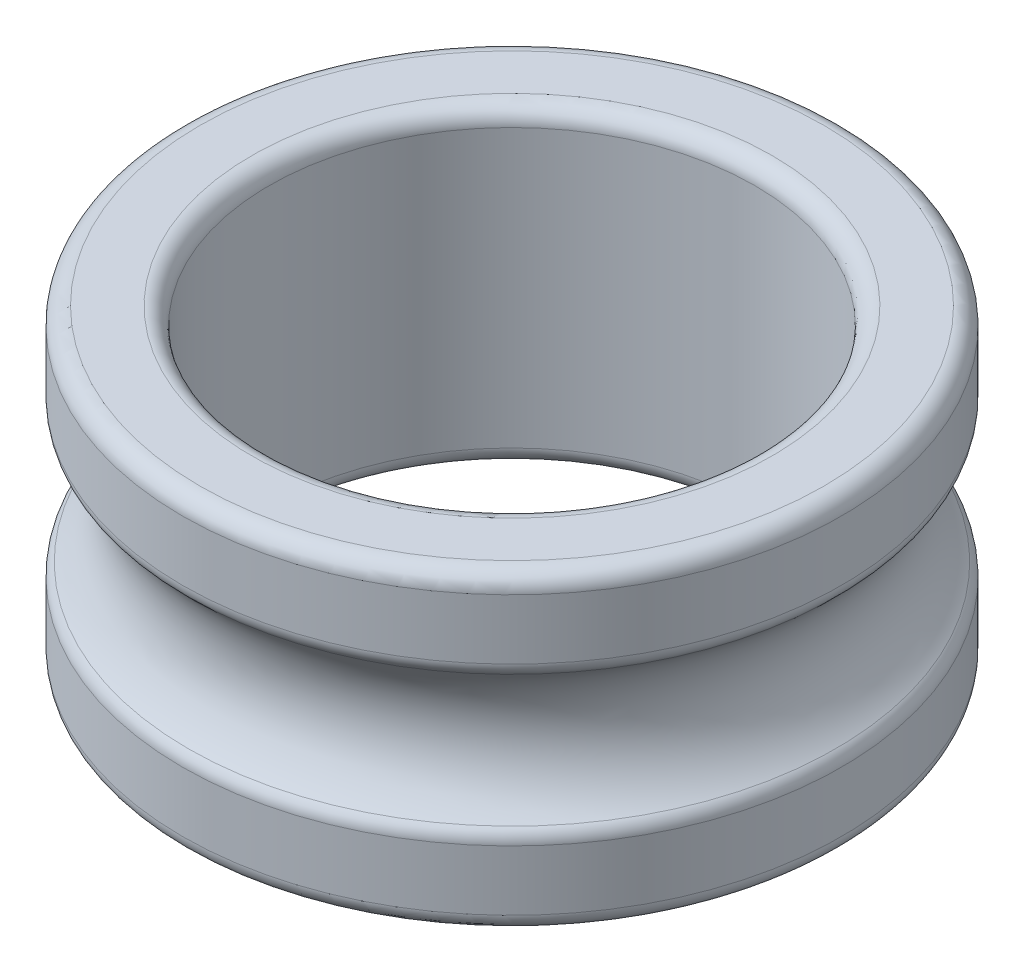
SolidWorks part; units mm, degrees
ref_plane "Front Plane" through (0, 0, 0) normal (0, 0, 1) x (1, 0, 0)
ref_plane "Top Plane" through (0, 0, 0) normal (0, 1, 0) x (1, 0, 0)
ref_plane "Right Plane" through (0, 0, 0) normal (1, 0, 0) x (0, 0, -1)
sketch "Sketch1" plane through (0, 0, 0) normal (1, 0, 0) x (0, 0, -1)
  line L0 (0, -9.8108) -> (0, 10.4568) construction
  line L1 (14, 8) -> (14, -8)
  line L2 (15, -9) -> (18, -9)
  line L3 (19, -8) -> (19, -4.539)
  line L4 (18, 9) -> (15, 9)
  line L5 (14, 0) -> (28.9693, 0) construction
  line L6 (19, 4.539) -> (19, 8)
  arc A0 (18.6612, 3.7888) -> (18.6612, -3.7888) centre (22, 0) ccw
  arc A1 (18.6612, -3.7888) -> (19, -4.539) centre (18, -4.539) cw
  arc A2 (18.6612, 3.7888) -> (19, 4.539) centre (18, 4.539) ccw
  arc A3 (18, -9) -> (19, -8) centre (18, -8) ccw
  arc A4 (14, -8) -> (15, -9) centre (15, -8) ccw
  arc A5 (19, 8) -> (18, 9) centre (18, 8) ccw
  arc A6 (14, 8) -> (15, 9) centre (15, 8) cw
  point P5 (14, 0)
  point P17 (19, 4.0623)
  dimension "D4" = 10.1
  dimension "D6" = 1
  dimension "D1" = 5
  dimension "D2" = 18
  dimension "D3" = 19
  dimension "D5" = 22
revolve "Revolve1" add sketch "Sketch1" angle 360 about L0
scale "Scale1" scale about centroid uniform scaling yes scale factor 0.266667
